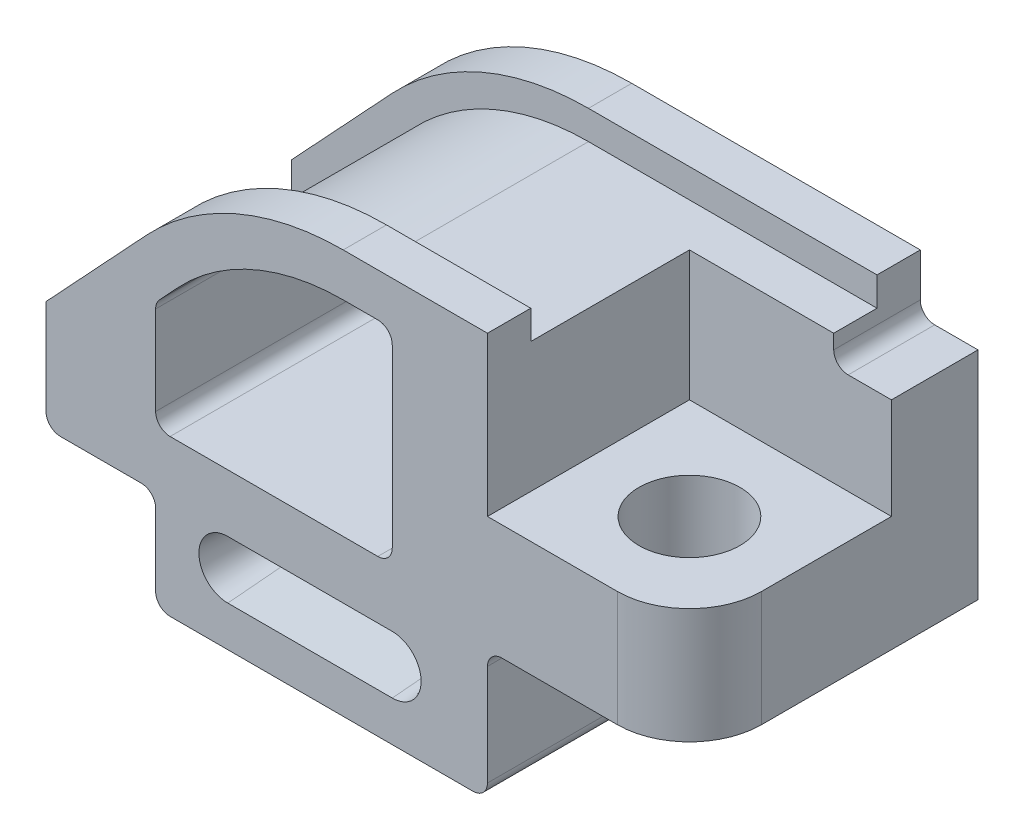
SolidWorks part; units mm, degrees
material "Copper"
ref_plane "Front Plane" through (0, 0, 0) normal (0, 0, 1) x (1, 0, 0)
ref_plane "Top Plane" through (0, 0, 0) normal (0, 1, 0) x (1, 0, 0)
ref_plane "Right Plane" through (0, 0, 0) normal (1, 0, 0) x (0, 0, -1)
sketch "Sketch1" plane through (0, 0, 0) normal (0, 0, 1) x (1, 0, 0)
  line L0 (0, 0) -> (-115, 0)
  line L1 (-115, 0) -> (-115, 35)
  line L2 (-115, 35) -> (-153, 35)
  line L3 (-153, 35) -> (-153, 73)
  line L5 (-50, 140) -> (50, 140)
  line L9 (70, 45) -> (0, 45)
  line L10 (0, 45) -> (0, 0)
  line L11 (-153, 73) -> (-118.1571, 110.3645)
  line L12 (70, 45) -> (70, 120)
  line L13 (70, 120) -> (50, 120)
  line L14 (50, 120) -> (50, 140)
  arc A0 (-50, 140) -> (-118.1571, 110.3645) centre (-50, 46.807) ccw
  point P9 (60, 120)
  point P14 (17.1564, 142.4918)
  point P16 (-156.4116, 75)
  dimension "D1" = 115
  dimension "D2" = 35
  dimension "D3" = 38
  dimension "D4" = 43
  dimension "D8" = 70
  dimension "D9" = 45
  dimension "D5" = 100
  dimension "D6" = 20
  dimension "D7" = 75
  dimension "D10" = 140
  dimension "D11" = 223
extrude "Boss-Extrude1" add sketch "Sketch1" along normal mid plane 100
sketch "Sketch2" plane through (0, 0, 50) normal (0, 0, 1) x (1, 0, 0)
  line L0 (-33, 54) -> (-33, 125)
  line L1 (0, 0) -> (0, 45) construction
  line L17 (-115, 91.7558) -> (-115, 54)
  line L18 (-107.1868, 100.1345) -> (-142.0297, 62.77)
  line L19 (-107.1868, 100.1345) -> (-115, 91.7558)
  line L20 (-115, 54) -> (-33, 54)
  line L24 (-115, 35) -> (-115, 0) construction
  line L25 (-50, 125) -> (-33, 125)
  arc A12 (-50, 125) -> (-107.1868, 100.1345) centre (-50, 46.807) ccw
  arc A13 (-50, 125) -> (-107.1868, 100.1345) centre (-50, 46.807) ccw
  dimension "D1" = 15
  dimension "D2" = 33
  dimension "D3" = 19
extrude "Cut-Extrude1" cut sketch "Sketch2" against normal offset from surface 15 and the other way through all up to face at (-38.9366, 72.5377, -50)
sketch "Sketch3" plane through (0, 140, 0) normal (0, 1, 0) x (1, 0, 0)
  line L1 (70, -50) -> (0, -50)
  line L2 (70, -50) -> (70, 20)
  line L3 (70, 20) -> (0, 20)
  line L4 (0, -50) -> (0, 20)
  dimension "D1" = 70
extrude "Cut-Extrude2" cut sketch "Sketch3" against normal blind 55
sketch "Sketch4" plane through (0, 85, 0) normal (0, 1, 0) x (1, 0, 0)
  line L0 (70, -50) -> (70, 20) construction
  line L1 (0, -50) -> (70, -50) construction
  line L2 (35, -50) -> (35, 20) construction
  line L3 (70, 20) -> (0, 20) construction
  line L4 (70, -25) -> (70, -50)
  line L5 (70, -50) -> (45, -50)
  circle A0 centre (35, -15) radius 17.5
  arc A1 (45, -50) -> (70, -25) centre (45, -25) ccw
  point P5 (70, -15)
  dimension "D1" = 35
  dimension "D2" = 25
extrude "Cut-Extrude3" cut sketch "Sketch4" against normal through all
sketch "Sketch5" plane through (0, 0, 0) normal (0, 0, 1) x (1, 0, 0)
  line L6 (50, 140) -> (50, 120) construction
  line L7 (50, 140) -> (0, 140) construction
  line L8 (-118.1571, 110.3645) -> (-153, 73) construction
  line L9 (-143, 69.0609) -> (-143, 35)
  line L10 (-110.8435, 103.5445) -> (-143, 69.0609)
  line L11 (0, 130) -> (-50, 130)
  line L12 (50, 130) -> (0, 130)
  line L14 (-110.8435, 103.5445) -> (-153, 58.3372)
  line L15 (0, 130) -> (-50, 130)
  line L16 (50, 130) -> (0, 130)
  line L17 (50, 140) -> (50, 130)
  line L18 (50, 140) -> (0, 140)
  line L19 (-118.1571, 110.3645) -> (-153, 73)
  line L21 (0, 140) -> (-50, 140) construction
  line L22 (0, 140) -> (-50, 140)
  line L25 (-153, 73) -> (-153, 35) construction
  line L26 (-153, 73) -> (-153, 58.3372)
  arc A1 (-50, 140) -> (-118.1571, 110.3645) centre (-50, 46.807) ccw construction
  arc A2 (-50, 130) -> (-110.8435, 103.5445) centre (-50, 46.807) ccw
  arc A3 (-50, 130) -> (-110.8435, 103.5445) centre (-50, 46.807) ccw
  arc A4 (-50, 140) -> (-118.1571, 110.3645) centre (-50, 46.807) ccw
  point P1 (-155, 60.8302)
  dimension "D1" = 10
extrude "Cut-Extrude4" cut sketch "Sketch5" against normal mid plane 70
fillet "Fillet1" radius 5 4 edges at (-33, 54, 7.5) (-33, 125, 7.5) (-115, 91.7558, 7.5) (-115, 54, 7.5)
fillet "Fillet2" radius 5 6 edges at (50, 120, -35) (0, 45, 0) (0, 0, 0) (-153, 35, 0) (-115, 0, 0) (-115, 35, 0)
sketch "Sketch6" plane through (0, 0, 50) normal (0, 0, 1) x (1, 0, 0)
  line L0 (-90, 24) -> (-33, 24) construction
  line L1 (-90, 34) -> (-33, 34)
  line L2 (-90, 14) -> (-33, 14)
  line L3 (-115, 30) -> (-115, 5) construction
  line L4 (-110, 54) -> (-38, 54) construction
  arc A0 (-90, 34) -> (-90, 14) centre (-90, 24) ccw
  arc A1 (-33, 14) -> (-33, 34) centre (-33, 24) ccw
  point P2 (-61.5, 24)
  point P7 (0, 0)
  point P8 (-56.1096, 24.7972)
  dimension "D3" = 10
  dimension "D1" = 57
  dimension "D2" = 25
  dimension "D4" = 20
extrude "Cut-Extrude5" cut sketch "Sketch6" against normal blind 25 draft 5
mirror "Mirror1" about plane through (0, 0, 0) normal (0, 0, 1) of "Cut-Extrude5"
equation "\"A\" = 223"
equation "\"B\" = 38"
equation "\"C\" = 35"
equation "\"D\" = 43"
equation "\"D3@Sketch1\"=\"B\""
equation "\"D4@Sketch1\"=\"D\""
equation "\"D11@Sketch1\"=\"A\""
equation "\"D1@Sketch4\"=\"C\""
